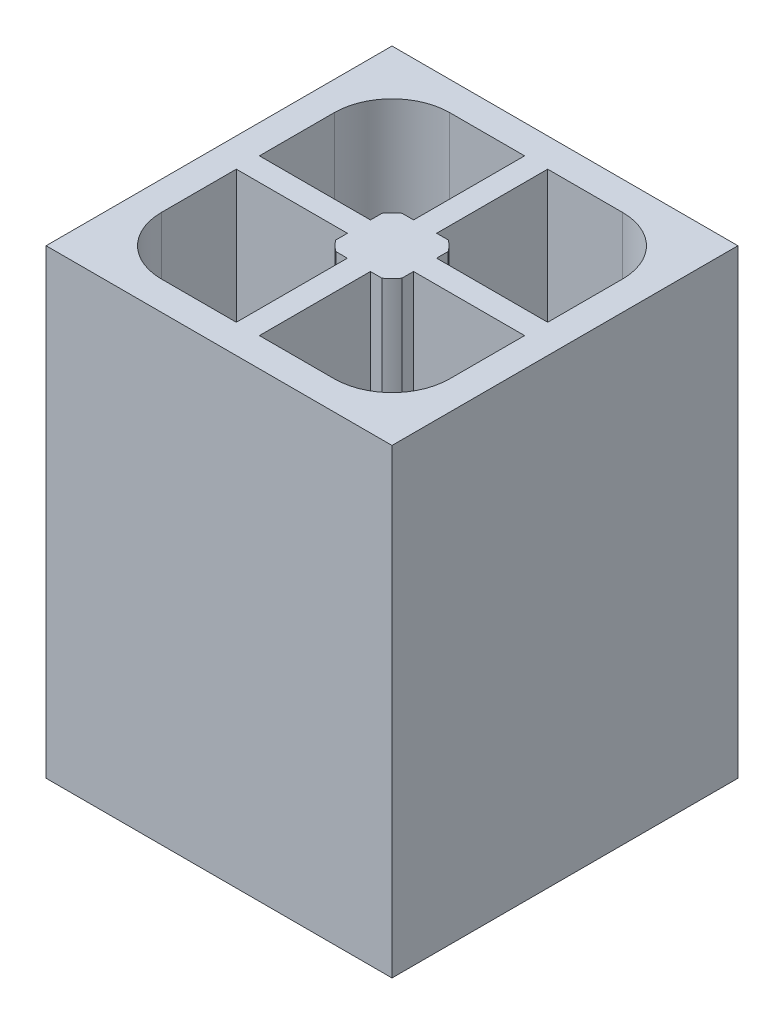
SolidWorks part; units mm, degrees
ref_plane "Front Plane" through (0, 0, 0) normal (0, 0, 1) x (1, 0, 0)
ref_plane "Top Plane" through (0, 0, 0) normal (0, 1, 0) x (1, 0, 0)
ref_plane "Right Plane" through (0, 0, 0) normal (1, 0, 0) x (0, 0, -1)
sketch "Sketch2" plane through (0, 0, 0) normal (0, 1, 0) x (1, 0, 0)
  line L1 (0, 0) -> (60, 0)
  line L2 (0, 0) -> (0, 60)
  line L3 (0, 60) -> (60, 60)
  line L4 (60, 0) -> (60, 60)
  dimension "D1" = 60
  dimension "D2" = 60
extrude "Boss-Extrude2" add sketch "Sketch2" along normal blind 80
sketch "Sketch3" plane through (0, 80, 0) normal (0, 1, 0) x (1, 0, 0)
  line L0 (0, 60) -> (0, 0) construction
  line L1 (15, 55) -> (45, 55)
  line L2 (5, 45) -> (5, 15)
  line L3 (15, 5) -> (45, 5)
  line L4 (55, 45) -> (55, 15)
  line L5 (60, 60) -> (0, 60) construction
  line L6 (60, 0) -> (60, 60) construction
  line L7 (0, 0) -> (60, 0) construction
  line L13 (26, 34) -> (5, 34)
  line L14 (26, 26) -> (5, 26)
  line L15 (5, 34) -> (5, 26)
  line L17 (26, 34) -> (26, 55)
  line L18 (34, 34) -> (34, 55)
  line L19 (26, 55) -> (34, 55)
  line L21 (34, 26) -> (55, 26)
  line L22 (34, 34) -> (55, 34)
  line L23 (55, 26) -> (55, 34)
  line L25 (26, 26) -> (26, 5)
  line L26 (34, 26) -> (34, 5)
  line L27 (26, 5) -> (34, 5)
  arc A1 (5, 15) -> (15, 5) centre (15, 15) ccw
  arc A2 (45, 5) -> (55, 15) centre (45, 15) ccw
  arc A3 (45, 55) -> (55, 45) centre (45, 45) cw
  arc A4 (15, 55) -> (5, 45) centre (15, 45) ccw
  point P0 (26, 5)
  dimension "D1" = 5
  dimension "D5" = 10
  dimension "D2" = 5
  dimension "D3" = 5
  dimension "D4" = 5
extrude "Cut-Extrude1" cut sketch "Sketch3" against normal blind 80 contours L1 A4 L2 L13 L17 | A3 L1 L18 L22 L4 | L2 A1 L3 L25 L14 | L3 A2 L4 L21 L26
sketch "Sketch4" plane through (0, 0, 0) normal (0, -1, 0) x (1, 0, 0)
  circle A0 centre (30, -30) radius 7
extrude "Boss-Extrude3" add sketch "Sketch4" against normal blind 80
sketch "Sketch5" plane through (0, 0, 0) normal (0, -1, 0) x (1, 0, 0)
  line L0 (26, -24.2554) -> (26, -5) construction
  line L1 (26, -24.2554) -> (26, -5)
  line L2 (26, -24.2554) -> (28, -24.2554)
  line L3 (26, -5) -> (28, -5)
  line L4 (28, -24.2554) -> (28, -5)
  line L5 (0, -30) -> (60, -30) construction
  line L6 (34, -5) -> (32, -5)
  line L7 (34, -5) -> (34, -24.2554)
  line L8 (34, -24.2554) -> (32, -24.2554)
  line L9 (32, -5) -> (32, -24.2554)
  line L10 (55, -26) -> (35.7341, -26)
  line L11 (55, -26) -> (55, -28)
  line L12 (55, -28) -> (35.7341, -28)
  line L13 (35.7341, -26) -> (35.7341, -28)
  line L14 (0, -60) -> (0, 0) construction
  line L15 (60, 0) -> (60, -60) construction
  line L16 (30, 0) -> (30, -60) construction
  line L17 (0, 0) -> (60, 0) construction
  line L18 (60, -60) -> (0, -60) construction
  line L19 (55, -32) -> (35.7341, -32)
  line L20 (35.7341, -34) -> (35.7341, -32)
  line L21 (55, -34) -> (35.7341, -34)
  line L22 (55, -34) -> (55, -32)
  line L23 (34, -35.7446) -> (32, -35.7446)
  line L24 (32, -55) -> (32, -35.7446)
  line L25 (34, -55) -> (32, -55)
  line L26 (34, -55) -> (34, -35.7446)
  line L27 (26, -55) -> (28, -55)
  line L28 (28, -35.7446) -> (28, -55)
  line L29 (26, -35.7446) -> (28, -35.7446)
  line L30 (26, -35.7446) -> (26, -55)
  line L31 (5, -34) -> (5, -32)
  line L32 (5, -34) -> (24.2659, -34)
  line L33 (24.2659, -34) -> (24.2659, -32)
  line L34 (5, -32) -> (24.2659, -32)
  line L35 (5, -28) -> (24.2659, -28)
  line L36 (24.2659, -26) -> (24.2659, -28)
  line L37 (5, -26) -> (24.2659, -26)
  line L38 (5, -26) -> (5, -28)
  dimension "D1" = 2
  dimension "D2" = 2
  dimension "D3" = 2
extrude "Cut-Extrude2" cut sketch "Sketch5" against normal blind 80
